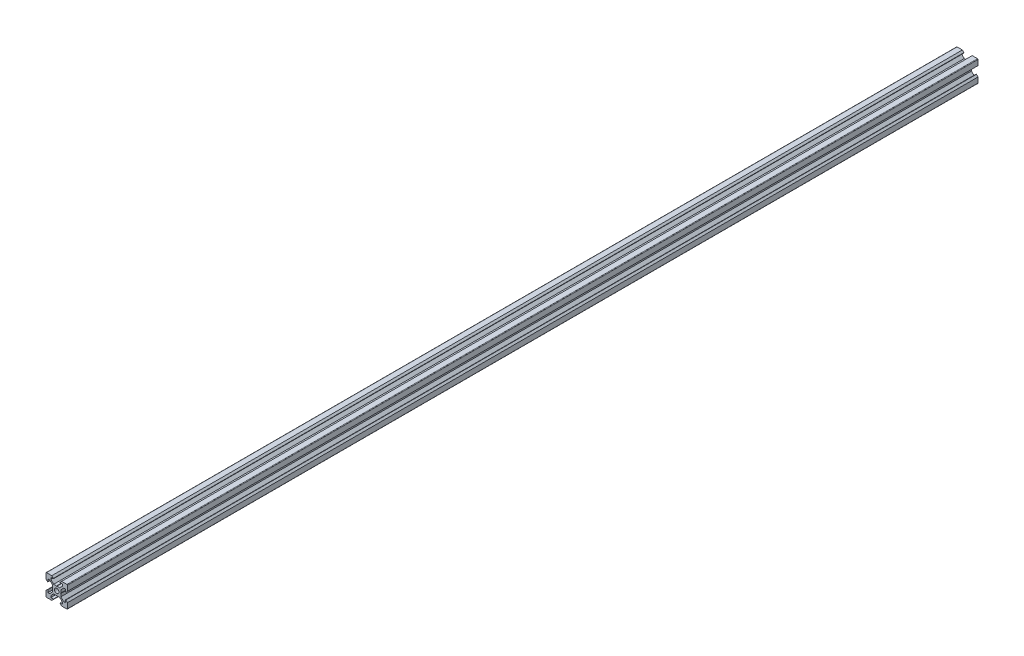
SolidWorks part; units mm, degrees
material "6061-T6 (SS)"
ref_plane "Front Plane" through (0, 0, 0) normal (0, 0, 1) x (1, 0, 0)
ref_plane "Top Plane" through (0, 0, 0) normal (0, 1, 0) x (1, 0, 0)
ref_plane "Right Plane" through (0, 0, 0) normal (1, 0, 0) x (0, 0, -1)
sketch "Sketch1" plane through (0, 0, 0) normal (0, 0, 1) x (1, 0, 0)
  line L1 (9.5, -10) -> (-9.5, -10)
  line L2 (10, -9.5) -> (10, 9.5)
  line L3 (9.5, 10) -> (-9.5, 10)
  line L4 (-10, -9.5) -> (-10, 9.5)
  line L5 (10, -10) -> (-10, 10) construction
  line L6 (10, 10) -> (-10, -10) construction
  circle A0 centre (0, 0) radius 2.1
  arc A1 (-9.5, 10) -> (-10, 9.5) centre (-9.5, 9.5) ccw
  arc A2 (10, 9.5) -> (9.5, 10) centre (9.5, 9.5) ccw
  arc A3 (9.5, -10) -> (10, -9.5) centre (9.5, -9.5) ccw
  arc A4 (-9.5, -10) -> (-10, -9.5) centre (-9.5, -9.5) cw
  point P0 (0, 0)
  line B0 (0, 0) -> (0, 10) construction
  line B1 (0, 3.69) -> (-0.21, 3.9)
  line B2 (-0.21, 3.9) -> (-2.8393, 3.9)
  line B3 (-2.8393, 3.9) -> (-5.5, 6.5607)
  line B4 (-5.5, 6.5607) -> (-5.5, 8.2)
  line B5 (-5.5, 8.2) -> (-3.125, 8.2)
  line B6 (-3.125, 8.2) -> (-3.125, 8.545)
  line B7 (-3.125, 8.545) -> (-4.58, 10)
  line B8 (-4.58, 10) -> (4.58, 10)
  line B9 (0, 0) -> (-5.9132, 5.9132) construction
  line B10 (3.125, 8.545) -> (4.58, 10)
  line B11 (3.125, 8.2) -> (3.125, 8.545)
  line B12 (5.5, 8.2) -> (3.125, 8.2)
  line B13 (5.5, 6.5607) -> (5.5, 8.2)
  line B14 (2.8393, 3.9) -> (5.5, 6.5607)
  line B15 (0.21, 3.9) -> (2.8393, 3.9)
  line B16 (0, 3.69) -> (0.21, 3.9)
  line B17 (0, 0) -> (-10, 0) construction
  line B18 (-3.69, 0) -> (-3.9, -0.21)
  line B19 (-3.9, -0.21) -> (-3.9, -2.8393)
  line B20 (-3.9, -2.8393) -> (-6.5607, -5.5)
  line B21 (-6.5607, -5.5) -> (-8.2, -5.5)
  line B22 (-8.2, -5.5) -> (-8.2, -3.125)
  line B23 (-8.2, -3.125) -> (-8.545, -3.125)
  line B24 (-8.545, -3.125) -> (-10, -4.58)
  line B25 (-10, -4.58) -> (-10, 4.58)
  line B26 (0, 0) -> (-5.9132, -5.9132) construction
  line B27 (-8.545, 3.125) -> (-10, 4.58)
  line B28 (-8.2, 3.125) -> (-8.545, 3.125)
  line B29 (-8.2, 5.5) -> (-8.2, 3.125)
  line B30 (-6.5607, 5.5) -> (-8.2, 5.5)
  line B31 (-3.9, 2.8393) -> (-6.5607, 5.5)
  line B32 (-3.9, 0.21) -> (-3.9, 2.8393)
  line B33 (-3.69, 0) -> (-3.9, 0.21)
  line B34 (0, 0) -> (0, -10) construction
  line B35 (0, -3.69) -> (0.21, -3.9)
  line B36 (0.21, -3.9) -> (2.8393, -3.9)
  line B37 (2.8393, -3.9) -> (5.5, -6.5607)
  line B38 (5.5, -6.5607) -> (5.5, -8.2)
  line B39 (5.5, -8.2) -> (3.125, -8.2)
  line B40 (3.125, -8.2) -> (3.125, -8.545)
  line B41 (3.125, -8.545) -> (4.58, -10)
  line B42 (4.58, -10) -> (-4.58, -10)
  line B43 (0, 0) -> (5.9132, -5.9132) construction
  line B44 (-3.125, -8.545) -> (-4.58, -10)
  line B45 (-3.125, -8.2) -> (-3.125, -8.545)
  line B46 (-5.5, -8.2) -> (-3.125, -8.2)
  line B47 (-5.5, -6.5607) -> (-5.5, -8.2)
  line B48 (-2.8393, -3.9) -> (-5.5, -6.5607)
  line B49 (-0.21, -3.9) -> (-2.8393, -3.9)
  line B50 (0, -3.69) -> (-0.21, -3.9)
  line B51 (0, 0) -> (10, 0) construction
  line B52 (3.69, 0) -> (3.9, 0.21)
  line B53 (3.9, 0.21) -> (3.9, 2.8393)
  line B54 (3.9, 2.8393) -> (6.5607, 5.5)
  line B55 (6.5607, 5.5) -> (8.2, 5.5)
  line B56 (8.2, 5.5) -> (8.2, 3.125)
  line B57 (8.2, 3.125) -> (8.545, 3.125)
  line B58 (8.545, 3.125) -> (10, 4.58)
  line B59 (10, 4.58) -> (10, -4.58)
  line B60 (0, 0) -> (5.9132, 5.9132) construction
  line B61 (8.545, -3.125) -> (10, -4.58)
  line B62 (8.2, -3.125) -> (8.545, -3.125)
  line B63 (8.2, -5.5) -> (8.2, -3.125)
  line B64 (6.5607, -5.5) -> (8.2, -5.5)
  line B65 (3.9, -2.8393) -> (6.5607, -5.5)
  line B66 (3.9, -0.21) -> (3.9, -2.8393)
  line B67 (3.69, 0) -> (3.9, -0.21)
  dimension "D1" = 4.2
  dimension "D3" = 0.5
  dimension "D2" = 20
sketch_block_instance "V Slot 1-4"
sketch_block "V Slot 1" parameters "D1"=10, "D2"=11, "D3"=4.3, "D4"=1.8, "D5"=0.21, "D6"=45, "D7"=9.16, "D8"=1.5, "D9"=6.25
sketch_block_instance "V Slot 1-5"
sketch_block_instance "V Slot 1-6"
sketch_block_instance "V Slot 1-7"
extrude "Boss-Extrude1" add sketch "Sketch1" along normal blind 850 contours B67 B52 B53 B54 B55 B56 B57 B58 L2 A2 L3 B10 B11 B12 B13 B14 B15 B16 B1 B2 B3 B4 B5 B6 B7 A1 L4 B27 B28 B29 B30 B31 B32 B33 B18 B19 B20 B21 B22 B23 B24 A4 L1 B44 B45 B46 B47 B48 B49
